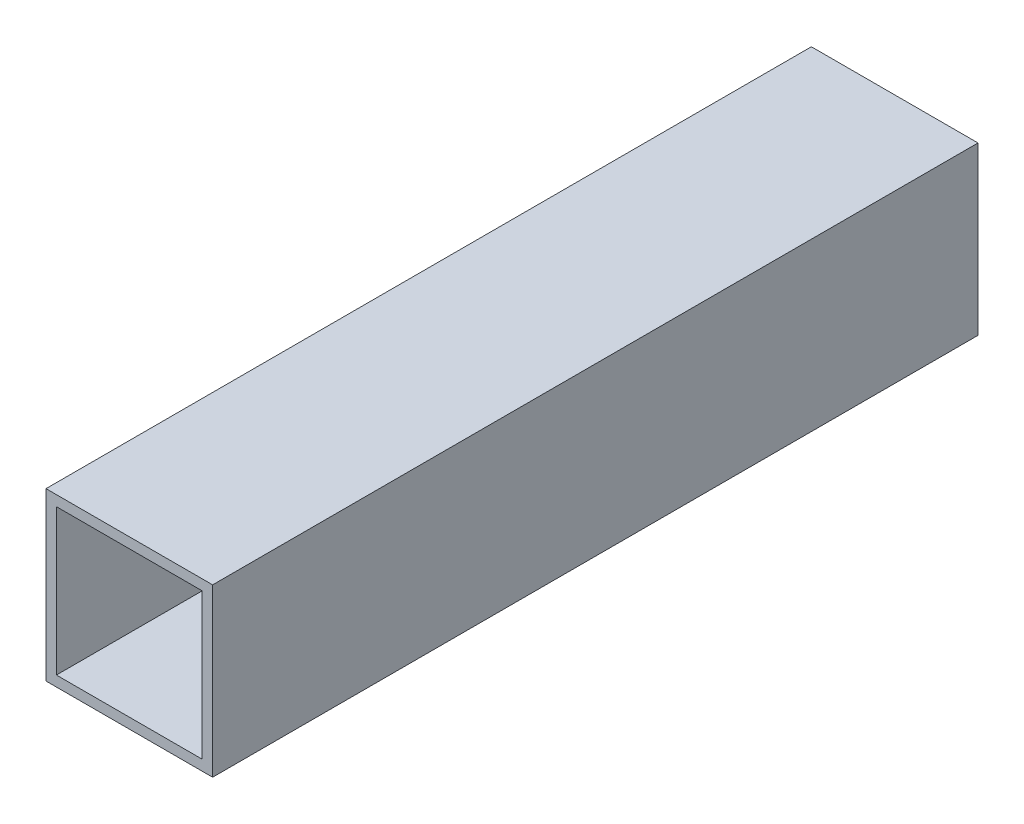
SolidWorks part; units mm, degrees
ref_plane "Alzado" through (0, 0, 0) normal (0, 0, 1) x (1, 0, 0)
ref_plane "Planta" through (0, 0, 0) normal (0, 1, 0) x (1, 0, 0)
ref_plane "Vista lateral" through (0, 0, 0) normal (1, 0, 0) x (0, 0, -1)
sketch "Croquis2" plane through (0, 0, 0) normal (0, 0, 1) x (1, 0, 0)
  line L0 (4.7625, -4.7625) -> (71.4375, -4.7625)
  line L1 (0, 0) -> (76.2, 0)
  line L2 (0, 0) -> (0, -76.2)
  line L3 (0, -76.2) -> (76.2, -76.2)
  line L4 (76.2, 0) -> (76.2, -76.2)
  line L5 (71.4375, -4.7625) -> (71.4375, -71.4375)
  line L6 (4.7625, -71.4375) -> (71.4375, -71.4375)
  line L7 (4.7625, -4.7625) -> (4.7625, -71.4375)
  dimension "D1" = 76.2
  dimension "D2" = 76.2
  dimension "D3" = 4.7625
extrude "Saliente-Extruir1" add sketch "Croquis2" against normal blind 350
